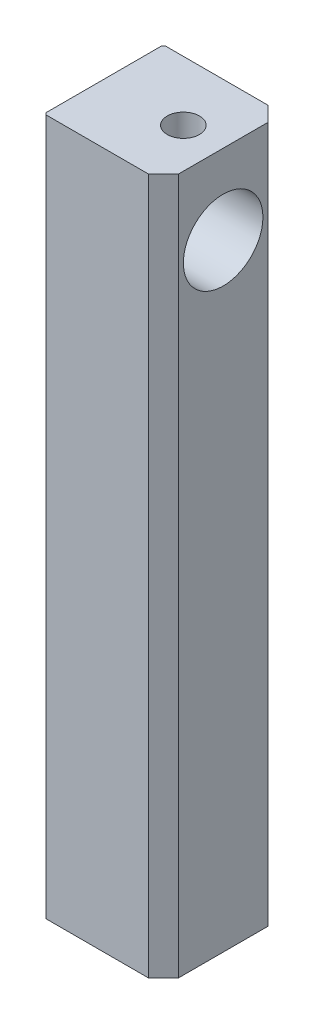
SolidWorks part; units mm, degrees
ref_plane "Front Plane" through (0, 0, 0) normal (0, 0, 1) x (1, 0, 0)
ref_plane "Top Plane" through (0, 0, 0) normal (0, 1, 0) x (1, 0, 0)
ref_plane "Right Plane" through (0, 0, 0) normal (1, 0, 0) x (0, 0, -1)
sketch "Sketch1" plane through (0, 0, 0) normal (0, 1, 0) x (1, 0, 0)
  line L0 (0, 6) -> (0, -6)
  line L2 (0, -6) -> (12, -6)
  line L4 (12, -6) -> (12, 6)
  line L6 (12, 6) -> (0, 6)
  dimension "MSM_1" = 12
extrude "Boss-Extrude1" add sketch "Sketch1" along normal blind 70
chamfer "Chamfer1" distance 0.2 2 edges at (0, 35, -6) (0, 35, 6)
chamfer "Chamfer2" distance 1.5 2 edges at (12, 35, -6) (12, 35, 6)
sketch "Sketch2" plane through (0, 0, 0) normal (1, 0, 0) x (0, 0, -1)
  line L1 (5.8, 70) -> (-5.8, 70) construction
  line L2 (5.8, 70) -> (-5.8, 70) construction
  circle A0 centre (0, 62) radius 4
  dimension "MSM_4" = 8
  dimension "MSM_5" = 8
extrude "Cut-Extrude1" cut sketch "Sketch2" along normal through all
hole_wizard "Tap1" positions "Sketch4" profile "Sketch3" hole size "M1x0.25" standard "JIS"
sketch "Sketch4" plane through (0, 70, 0) normal (0, 1, 0) x (1, 0, 0)
  point P0 (8, 0)
  dimension "MSM_6" = 8
sketch "Sketch3" plane through (8, 70, 0) normal (1, 0, 0) x (0, 0, 1)
  line L0 (0, 0) -> (0, 4)
  line L1 (0, 4) -> (1.621, 4)
  line L2 (1.621, 4) -> (1.621, 0)
  line L5 (1.621, 0) -> (0, 0)
  line L11 (0, -6.35) -> (0, 107.95) construction
  dimension "STD_1" = 3.242
  dimension "Thru Hole Depth" = 4
cosmetic thread "Thread1" parameters "HTD_1"=4
